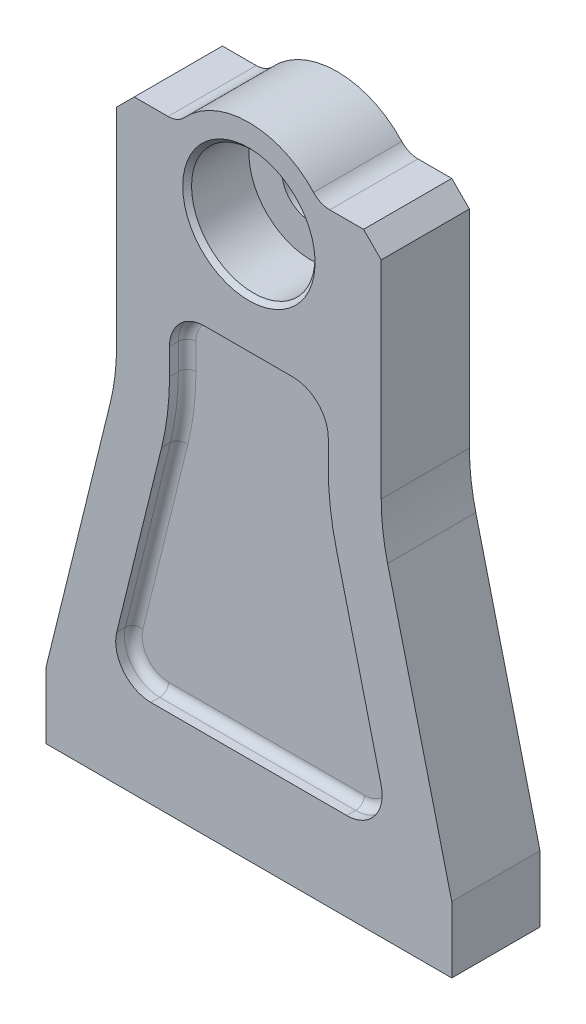
SolidWorks part; units mm, degrees
ref_plane "Front Plane" through (0, 0, 0) normal (0, 0, 1) x (1, 0, 0)
ref_plane "Top Plane" through (0, 0, 0) normal (0, 1, 0) x (1, 0, 0)
ref_plane "Right Plane" through (0, 0, 0) normal (1, 0, 0) x (0, 0, -1)
sketch "Sketch1" plane through (0, 0, 0) normal (0, 0, 1) x (1, 0, 0)
  line L0 (-46, 0) -> (46, 0)
  line L1 (46, 0) -> (46, 15)
  line L2 (46, 15) -> (31.4493, 74.1124)
  line L3 (30, 86.0633) -> (30, 137)
  line L4 (30, 137) -> (16, 137)
  line L5 (0, 0) -> (0, 85.5539) construction
  line L6 (-46, 0) -> (-46, 15)
  line L7 (-46, 15) -> (-31.4493, 74.1124)
  line L8 (-30, 86.0633) -> (-30, 137)
  line L9 (-30, 137) -> (-16, 137)
  circle A0 centre (0, 125) radius 6.5
  arc A1 (16, 137) -> (-16, 137) centre (0, 125) ccw
  arc A2 (31.4493, 74.1124) -> (30, 86.0633) centre (80, 86.0633) cw
  arc A3 (-31.4493, 74.1124) -> (-30, 86.0633) centre (-80, 86.0633) ccw
  point P17 (30, 80)
  point P20 (-30, 80)
  dimension "D2" = 13
  dimension "D3" = 40
  dimension "D9" = 50
  dimension "D1" = 125
  dimension "D4" = 46
  dimension "D5" = 15
  dimension "D6" = 65
  dimension "D7" = 12
  dimension "D8" = 30
extrude "Boss-Extrude1" add sketch "Sketch1" along normal mid plane 20
sketch "Sketch2" plane through (0, 0, 10) normal (0, 0, 1) x (1, 0, 0)
  circle A0 centre (0, 125) radius 14
extrude "Cut-Extrude1" cut sketch "Sketch2" against normal blind 14
chamfer "Chamfer1" distance 1 angle 45 1 edges at (14, 125, 10)
chamfer "Chamfer2" distance 4 angle 45 2 edges at (30, 137, 0) (-30, 137, 0)
fillet "Fillet1" radius 5 2 edges at (-16, 137, 0) (16, 137, 0)
sketch "Sketch3" plane through (0, 0, 10) normal (0, 0, 1) x (1, 0, 0)
  line L13 (-18, 133) -> (-18, 86.0633)
  line L14 (-19.7971, 71.2442) -> (-34.3478, 12.1318)
  line L15 (-18, 92) -> (-18, 86.0633)
  line L16 (-19.7971, 71.2442) -> (-29.9711, 29.9122)
  line L20 (-10, 100) -> (10, 100)
  line L21 (18, 86.0633) -> (18, 133)
  line L22 (34.3478, 12.1318) -> (19.7971, 71.2442)
  line L23 (18, 86.0633) -> (18, 92)
  line L24 (29.9711, 29.9122) -> (19.7971, 71.2442)
  line L25 (-46, 20) -> (46, 20)
  line L26 (-22.203, 20) -> (22.203, 20)
  line L27 (-46, 0) -> (46, 0) construction
  arc A6 (-19.7971, 71.2442) -> (-18, 86.0633) centre (-80, 86.0633) ccw
  arc A7 (-19.7971, 71.2442) -> (-18, 86.0633) centre (-80, 86.0633) ccw
  arc A9 (-29.9711, 29.9122) -> (-22.203, 20) centre (-22.203, 28) ccw
  arc A10 (18, 86.0633) -> (19.7971, 71.2442) centre (80, 86.0633) ccw
  arc A11 (18, 86.0633) -> (19.7971, 71.2442) centre (80, 86.0633) ccw
  arc A12 (22.203, 20) -> (29.9711, 29.9122) centre (22.203, 28) ccw
  arc A13 (18, 92) -> (10, 100) centre (10, 92) ccw
  arc A14 (-18, 92) -> (-10, 100) centre (-10, 92) cw
  dimension "D5" = 8
  dimension "D4" = 100
  dimension "D1" = 12
  dimension "D2" = 12
  dimension "D3" = 20
extrude "Cut-Extrude2" cut sketch "Sketch3" against normal blind 4
fillet "Fillet2" radius 2 12 edges at (-24.8841, 50.5782, 6) (-18.4509, 78.5995, 6) (-18, 89.0317, 6) (-15.6569, 97.6569, 6) (0, 100, 6) (15.6569, 97.6569, 6) (18, 89.0317, 6) (18.4509, 78.5995, 6) (24.8841, 50.5782, 6) (28.4997, 23.0653, 6) (0, 20, 6) (-28.4997, 23.0653, 6)
mirror "Mirror1" about plane through (0, 0, 0) normal (0, 0, 1) of "Fillet2", "Cut-Extrude2"
hole_wizard "M10x1.25 Tapped Hole1" positions "Sketch4" profile "Sketch5" tap size "M10x1.25" standard "ISO"
sketch "Sketch4" plane through (0, 0, 0) normal (0, -1, 0) x (-1, 0, 0)
  line L0 (-46, -10) -> (-46, 10) construction
  point P0 (-30, 0)
  point P2 (30, 0)
  dimension "D1" = 60
  dimension "D2" = 16
sketch "Sketch5" plane through (30, 0, 0) normal (1, 0, 0) x (0, 0, -1)
  line L0 (0, 0) -> (0, 22.6438)
  line L1 (0, 22.6438) -> (4.4, 20)
  line L2 (4.4, 20) -> (4.4, 0.625)
  line L3 (4.4, 0.625) -> (5.025, 0)
  line L5 (5.025, 0) -> (0, 0)
  line L6 (-4.4, 0.625) -> (-5.025, 0) construction
  line L10 (0, 22.6438) -> (-4.4, 20) construction
  line L11 (0, -6.35) -> (0, 107.95) construction
  dimension "Tap Drill Dia." = 8.8
  dimension "Tap Drill Depth" = 20
  dimension "Near C'Sink Dia." = 10.05
  dimension "Near C'Sink Angle" = 90
  dimension "Drill Angle" = 118
cosmetic thread "Hole Thread1" parameters "D1"=20, "D2"=10
cosmetic thread "Hole Thread2" parameters "D1"=20, "D2"=10
